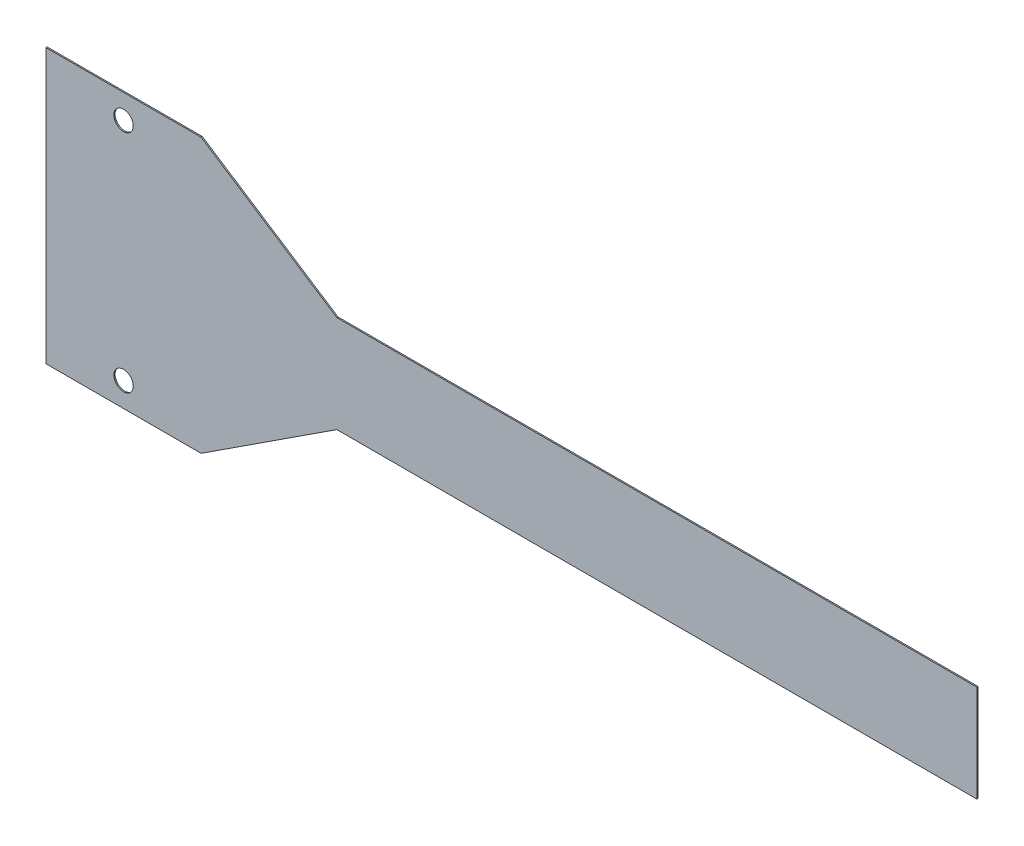
SolidWorks part; units mm, degrees
ref_plane "Front Plane" through (0, 0, 0) normal (0, 0, 1) x (1, 0, 0)
ref_plane "Top Plane" through (0, 0, 0) normal (0, 1, 0) x (1, 0, 0)
ref_plane "Right Plane" through (0, 0, 0) normal (1, 0, 0) x (0, 0, -1)
sketch "Sketch1" plane through (0, 0, 0) normal (0, 0, 1) x (1, 0, 0)
  line L0 (0, -9.12) -> (16, -9.12)
  line L1 (16, -9.12) -> (30, 0)
  line L2 (30, 0) -> (96, 0)
  line L3 (96, 0) -> (96, 10)
  line L4 (96, 10) -> (30, 10)
  line L5 (30, 10) -> (16, 19.12)
  line L6 (16, 19.12) -> (0, 19.12)
  line L7 (0, 19.12) -> (0, -9.12)
  circle A0 centre (8, -6.62) radius 1
  circle A1 centre (8, 16.62) radius 1
  dimension "D4" = 2
  dimension "D6" = 2
  dimension "D1" = 10
  dimension "D2" = 96
  dimension "D3" = 28.24
  dimension "D5" = 8
  dimension "D7" = 8
extrude "Boss-Extrude1" add sketch "Sketch1" along normal blind 0.125
sketch "Sketch2" plane through (0, 0, 0) normal (0, 0, 1) x (1, 0, 0)
  line L0 (5, -4.12) -> (5, -1.12)
  line L1 (5, -1.12) -> (11, -1.12)
  line L2 (11, -1.12) -> (11, -2.12)
  line L3 (11, -2.12) -> (30, 1.5)
  line L4 (30, 1.5) -> (86, 1.5)
  line L5 (86, 1.5) -> (86, 4.5)
  line L6 (86, 4.5) -> (86, 5.5)
  line L7 (86, 5.5) -> (87, 5.5)
  line L8 (87, 5.5) -> (93, 5.5)
  line L9 (93, 5.5) -> (93, 4.5)
  line L10 (93, 4.5) -> (87, 4.5)
  line L11 (87, 4.5) -> (87, 1.5)
  line L12 (87, 1.5) -> (87, 0.5)
  line L13 (87, 0.5) -> (86, 0.5)
  line L14 (86, 0.5) -> (30, 0.5)
  line L15 (30, 0.5) -> (11, -3.12)
  line L16 (11, -3.12) -> (11, -4.12)
  line L17 (11, -4.12) -> (5, -4.12)
  line L18 (5, 0.96) -> (5, 3.96)
  line L19 (5, 3.96) -> (11, 3.96)
  line L20 (11, 3.96) -> (11, 2.96)
  line L21 (11, 2.96) -> (30, 3.5)
  line L22 (30, 3.5) -> (68.5, 3.5)
  line L23 (68.5, 3.5) -> (68.5, 4.5)
  line L24 (68.5, 4.5) -> (68.5, 5.5)
  line L25 (68.5, 5.5) -> (69.5, 5.5)
  line L26 (69.5, 5.5) -> (75.5, 5.5)
  line L27 (75.5, 5.5) -> (75.5, 4.5)
  line L28 (75.5, 4.5) -> (69.5, 4.5)
  line L29 (69.5, 4.5) -> (69.5, 3.5)
  line L30 (69.5, 3.5) -> (69.5, 2.5)
  line L31 (69.5, 2.5) -> (68.5, 2.5)
  line L32 (68.5, 2.5) -> (30, 2.5)
  line L33 (30, 2.5) -> (11, 1.96)
  line L34 (11, 1.96) -> (11, 0.96)
  line L35 (11, 0.96) -> (5, 0.96)
  line L36 (94.5, 6.5) -> (93.5, 6.5)
  line L37 (93.5, 6.5) -> (30, 6.5)
  line L38 (30, 6.5) -> (11, 7.04)
  line L39 (11, 7.04) -> (11, 6.04)
  line L40 (11, 6.04) -> (5, 6.04)
  line L41 (5, 6.04) -> (5, 9.04)
  line L42 (5, 9.04) -> (11, 9.04)
  line L43 (11, 9.04) -> (11, 8.04)
  line L44 (11, 8.04) -> (30, 7.5)
  line L45 (30, 7.5) -> (93.5, 7.5)
  line L46 (93.5, 7.5) -> (93.5, 8.3)
  line L47 (93.5, 8.3) -> (30, 8.3)
  line L48 (30, 8.3) -> (11, 12.12)
  line L49 (11, 12.12) -> (11, 11.12)
  line L50 (11, 11.12) -> (5, 11.12)
  line L51 (5, 11.12) -> (5, 14.12)
  line L52 (5, 14.12) -> (11, 14.12)
  line L53 (11, 14.12) -> (11, 13.12)
  line L54 (11, 13.12) -> (30, 9.3)
  line L55 (30, 9.3) -> (93.5, 9.3)
  line L56 (93.5, 9.3) -> (94.5, 9.3)
  line L57 (94.5, 9.3) -> (94.5, 8.3)
  line L58 (94.5, 8.3) -> (94.5, 7.5)
  line L59 (94.5, 7.5) -> (94.5, 6.5)
extrude "Boss-Extrude2" add sketch "Sketch2" against normal blind 0.02 separate body
